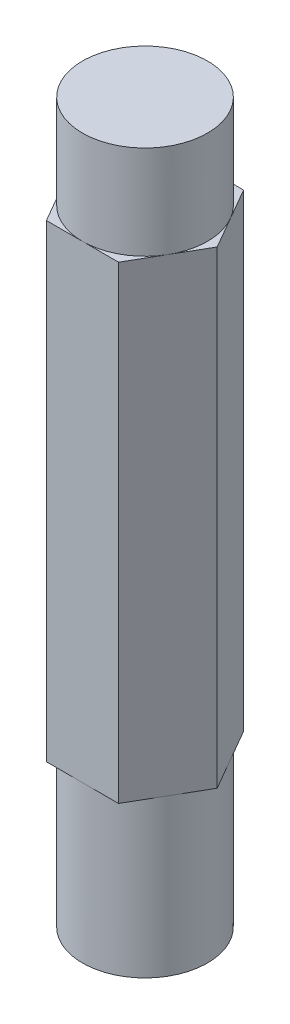
SolidWorks part; units mm, degrees
ref_plane "Front Plane" through (0, 0, 0) normal (0, 0, 1) x (1, 0, 0)
ref_plane "Top Plane" through (0, 0, 0) normal (0, 1, 0) x (1, 0, 0)
ref_plane "Right Plane" through (0, 0, 0) normal (1, 0, 0) x (0, 0, -1)
sketch "Sketch1" plane through (0, 0, 0) normal (0, 1, 0) x (1, 0, 0)
  line L1 (-2.3094, 0) -> (-1.1547, -2)
  line L2 (-1.1547, -2) -> (1.1547, -2)
  line L3 (1.1547, -2) -> (2.3094, 0)
  line L4 (2.3094, 0) -> (1.1547, 2)
  line L5 (1.1547, 2) -> (-1.1547, 2)
  line L6 (-1.1547, 2) -> (-2.3094, 0)
  circle A0 centre (0, 0) radius 2 construction
  dimension "D1" = 4
extrude "Boss-Extrude1" add sketch "Sketch1" along normal mid plane 15
sketch "Sketch2" plane through (0, 7.5, 0) normal (0, 1, 0) x (1, 0, 0)
  line L0 (-1.1547, 2) -> (-2.3094, 0) construction
  circle A0 centre (0, 0) radius 2
extrude "Boss-Extrude3" add sketch "Sketch2" along normal blind 3 contours A0
sketch "Sketch4" plane through (0, -7.5, 0) normal (0, -1, 0) x (1, 0, 0)
  line L0 (-2.3094, 0) -> (-1.1547, 2) construction
  circle A0 centre (0, 0) radius 2
extrude "Boss-Extrude4" add sketch "Sketch4" along normal blind 5
